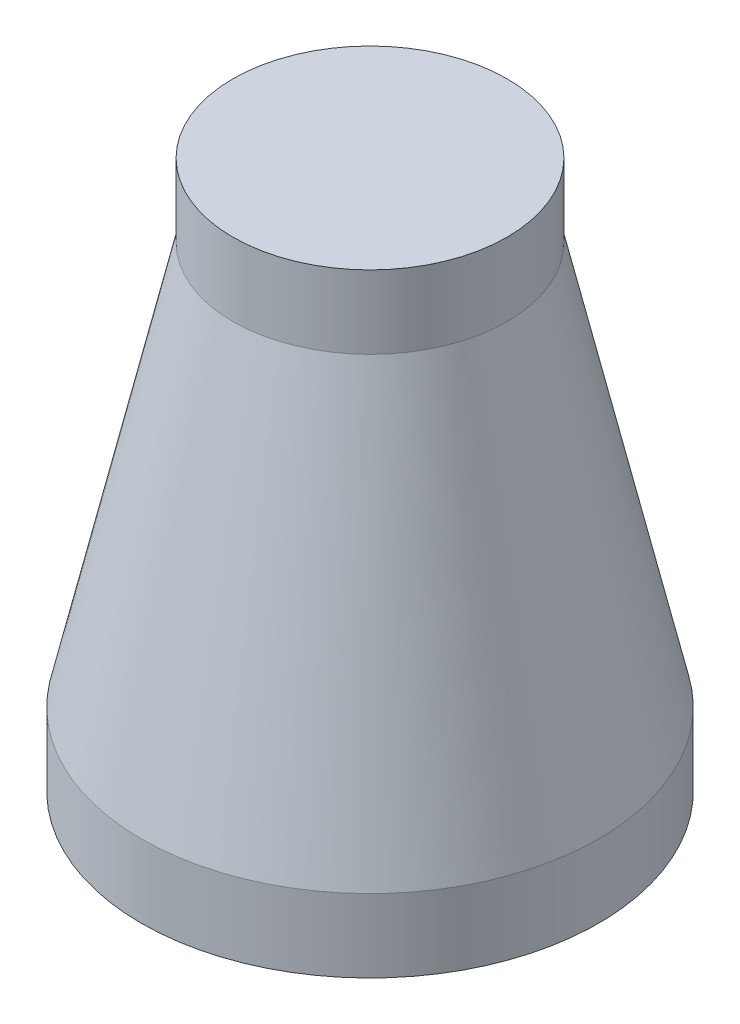
SolidWorks part; units mm, degrees
ref_plane "前视基准面" through (0, 0, 0) normal (0, 0, 1) x (1, 0, 0)
ref_plane "上视基准面" through (0, 0, 0) normal (0, 1, 0) x (1, 0, 0)
ref_plane "右视基准面" through (0, 0, 0) normal (1, 0, 0) x (0, 0, -1)
other "Configuration Table"
sketch "草图1" plane through (0, 0, 0) normal (0, 0, 1) x (1, 0, 0)
  line L0 (0, 0) -> (0, 60)
  line L1 (0, 60) -> (15, 60)
  line L2 (15, 60) -> (15, 52)
  line L3 (15, 52) -> (25, 8)
  line L4 (25, 8) -> (25, 0)
  line L5 (25, 0) -> (0, 0)
  dimension "D1" = 8
  dimension "D2" = 8
  dimension "D3" = 60
  dimension "D4" = 15
  dimension "D5" = 25
revolve "旋转1" add sketch "草图1" angle 360 about L0
